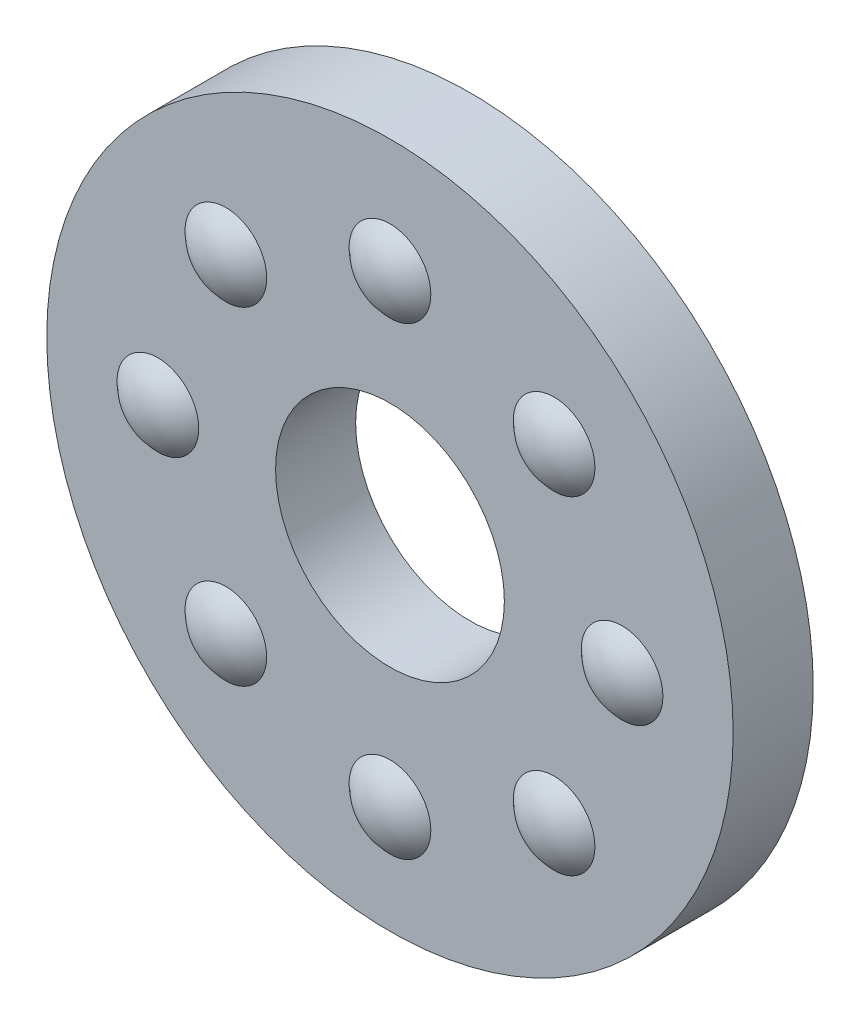
SolidWorks part; units mm, degrees
material "黄铜"
ref_plane "前视基准面" through (0, 0, 0) normal (0, 0, 1) x (1, 0, 0)
ref_plane "上视基准面" through (0, 0, 0) normal (0, 1, 0) x (1, 0, 0)
ref_plane "右视基准面" through (0, 0, 0) normal (1, 0, 0) x (0, 0, -1)
sketch "草图1" plane through (0, 0, 0) normal (0, 0, 1) x (1, 0, 0)
  circle A0 centre (0, 0) radius 3
  dimension "D1" = 6
extrude "凸台-拉伸1" add sketch "草图1" along normal blind 0.7
ref_plane "基准面1" through (0, 0, 0.35) normal (0, 0, 1) x (1, 0, 0)
sketch "草图2" plane through (0, 0, 0.35) normal (0, 0, 1) x (1, 0, 0)
  line L0 (0, 2.5) -> (0, 1.5)
  arc A0 (0, 2.5) -> (0, 1.5) centre (0, 2) ccw
  point P4 (0, 0)
  dimension "D1" = 1
  dimension "D2" = 2
revolve "旋转1" add sketch "草图2" angle 360 about L0
pattern_circular "阵列(圆周)1" count 8 every 45 about axis through (0, -0.0287, 0) along (0, 0, 1) of "旋转1"
sketch "草图3" plane through (0, 0, 0.7) normal (0, 0, 1) x (1, 0, 0)
  circle A0 centre (0, 0) radius 1
  dimension "D1" = 2
extrude "切除-拉伸1" cut sketch "草图3" against normal through all
